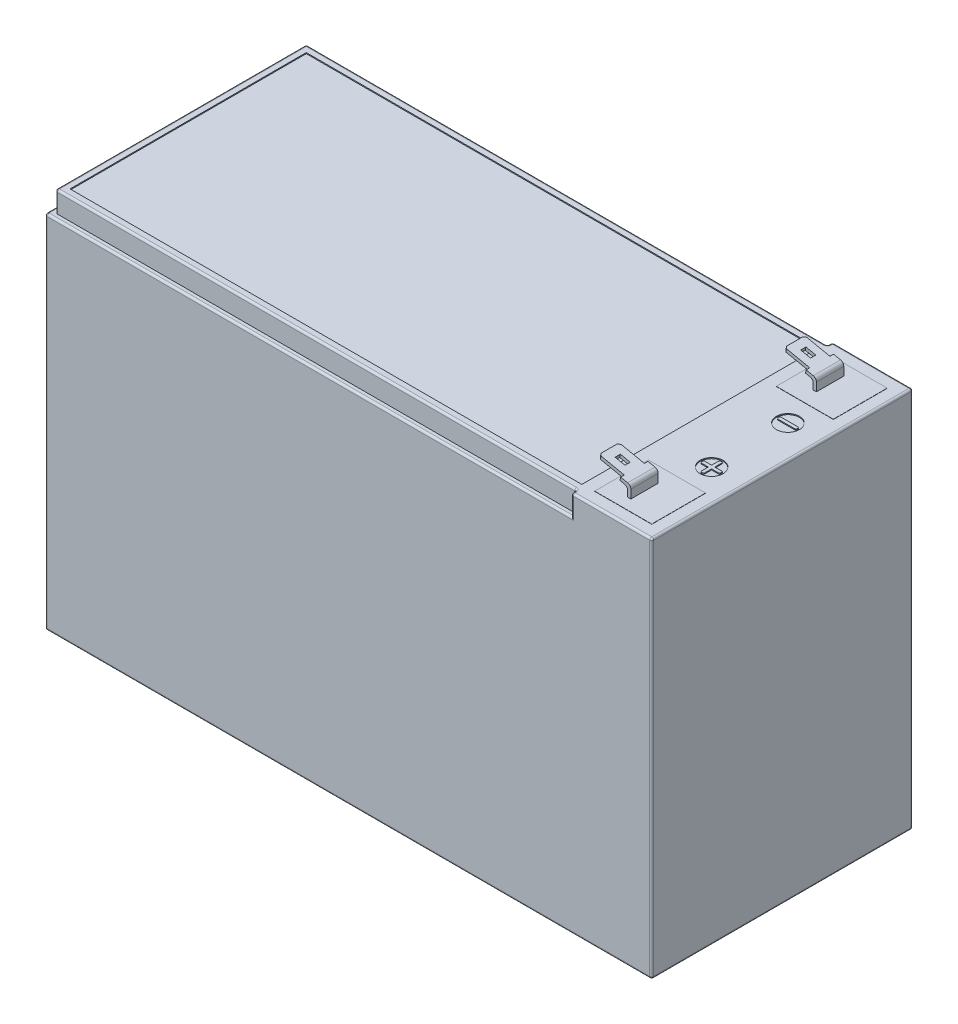
SolidWorks part; units mm, degrees
ref_plane "Front Plane" through (0, 0, 0) normal (0, 0, 1) x (1, 0, 0)
ref_plane "Top Plane" through (0, 0, 0) normal (0, 1, 0) x (1, 0, 0)
ref_plane "Right Plane" through (0, 0, 0) normal (1, 0, 0) x (0, 0, -1)
sketch "Sketch1" plane through (0, 0, 0) normal (0, 1, 0) x (1, 0, 0)
  line L1 (-75.0564, 43.5611) -> (75.9436, 43.5611)
  line L2 (-75.0564, 43.5611) -> (-75.0564, -21.4389)
  line L3 (-75.0564, -21.4389) -> (75.9436, -21.4389)
  line L4 (75.9436, 43.5611) -> (75.9436, -21.4389)
  dimension "D1" = 151
  dimension "D2" = 65
extrude "Boss-Extrude1" add sketch "Sketch1" along normal blind 95
ref_plane "Plane1" through (0, 0, 15.4389) normal (0, 0, 1) x (1, 0, 0)
sketch "Sketch2" plane through (0, 0, 15.4389) normal (0, 0, 1) x (1, 0, 0)
  line L0 (63.9436, 95) -> (63.9436, 97.3257)
  line L1 (-75.0564, 95) -> (75.9436, 95) construction
  line L2 (63.9436, 97.3257) -> (55.7698, 99.03)
  line L3 (55.7698, 99.03) -> (55.9331, 99.8131)
  line L4 (55.9331, 99.8131) -> (64.7436, 97.9761)
  line L5 (64.7436, 97.9761) -> (64.7436, 95)
  line L6 (64.7436, 95) -> (63.9436, 95)
  line L7 (75.9436, 95) -> (75.9436, 0) construction
  dimension "D1" = 12
  dimension "D2" = 9
  dimension "D3" = 0.8
  dimension "D4" = 0.8
extrude "Boss-Extrude2" add sketch "Sketch2" against normal blind 6.8
ref_plane "Plane2" through (0, 0, -11.0611) normal (0, 0, 1) x (1, 0, 0)
sketch "Sketch4" plane through (22.274, 106.8309, 0) normal (0.2041, 0.9789, 0) x (0.9789, -0.2041, 0)
  line L0 (40.7829, -8.6389) -> (40.7829, -9.5389)
  line L1 (43.3829, -8.6389) -> (34.3829, -8.6389) construction
  line L2 (40.7829, -9.5389) -> (34.3829, -9.5389)
  line L3 (34.3829, -8.6389) -> (34.3829, -15.4389) construction
  line L4 (34.3829, -9.5389) -> (34.3829, -8.6389)
  line L5 (34.3829, -8.6389) -> (40.7829, -8.6389)
  line L6 (40.7829, -14.5389) -> (40.7829, -15.4389)
  line L7 (-52.25, -15.4389) -> (52.25, -15.4389) construction
  line L8 (40.7829, -14.5389) -> (34.3829, -14.5389)
  line L9 (34.3829, -14.5389) -> (34.3829, -15.4389)
  line L10 (34.3829, -15.4389) -> (40.7829, -15.4389)
  line L12 (36.5829, -11.3889) -> (39.0829, -11.3889)
  line L13 (36.5829, -11.3889) -> (36.5829, -12.6889)
  line L14 (36.5829, -12.6889) -> (39.0829, -12.6889)
  line L15 (39.0829, -11.3889) -> (39.0829, -12.6889)
  dimension "D1" = 0.9
  dimension "D2" = 0.9
  dimension "D3" = 6.4
  dimension "D4" = 2.2
  dimension "D5" = 2.5
  dimension "D6" = 1.3
  dimension "D7" = 1.85
  dimension "D8" = 1.85
extrude "Cut-Extrude1" cut sketch "Sketch4" against normal up to next
chamfer "Chamfer1" distance 0.5 angle 45 2 edges at (55.8514, 99.4215, 9.5389) (55.8514, 99.4215, 14.5389)
fillet "Fillet1" radius 1 2 edges at (63.9436, 97.3257, 12.0389) (64.7436, 97.9761, 12.0389)
mirror "Mirror1" about plane through (0, 0, -11.0611) normal (0, 0, 1) of "Fillet1", "Chamfer1", "Cut-Extrude1", "Boss-Extrude2"
sketch "Sketch5" plane through (0, 95, 0) normal (0, 1, 0) x (1, 0, 0)
  line L0 (55.9436, -21.4389) -> (55.9436, -20.1389)
  line L1 (-75.0564, -21.4389) -> (75.9436, -21.4389) construction
  line L2 (55.9436, -20.1389) -> (-73.7564, -20.1389)
  line L3 (-73.7564, -20.1389) -> (-73.7564, 42.2611)
  line L4 (-73.7564, 42.2611) -> (55.9436, 42.2611)
  line L5 (55.9436, 42.2611) -> (55.9436, 43.5611)
  line L6 (75.9436, 43.5611) -> (-75.0564, 43.5611) construction
  line L7 (55.9436, 43.5611) -> (-75.0564, 43.5611)
  line L8 (-75.0564, 43.5611) -> (-75.0564, -21.4389)
  line L9 (-75.0564, -21.4389) -> (55.9436, -21.4389)
  line L10 (75.9436, -21.4389) -> (75.9436, 43.5611) construction
  dimension "D1" = 1.3
  dimension "D2" = 1.3
  dimension "D3" = 1.3
  dimension "D4" = 20
  dimension "D5" = 20
extrude "Cut-Extrude2" cut sketch "Sketch5" against normal blind 5.2
fillet "Fillet2" radius 0.5 25 edges at (0.4436, 0, -43.5611) (-75.0564, 44.9, -43.5611) (-75.0564, 0, -11.0611) (-75.0564, 44.9, 21.4389) (75.9436, 0, -11.0611) (0.4436, 0, 21.4389) (75.9436, 47.5, -43.5611) (65.9436, 95, -43.5611) (55.9436, 92.4, -43.5611) (55.9436, 92.4, -42.2611) (55.9436, 95, -42.9111) (-9.5564, 89.8, -43.5611) (-8.9064, 95, -42.2611) (-73.7564, 92.4, -42.2611) (-73.7564, 92.4, 20.1389) (-75.0564, 89.8, -11.0611) (55.9436, 92.4, 20.1389) (-9.5564, 89.8, 21.4389) (55.9436, 92.4, 21.4389) (75.9436, 47.5, 21.4389) (75.9436, 95, -11.0611) (65.9436, 95, 21.4389) (55.9436, 95, 20.7889) (-8.9064, 95, 20.1389) (-73.7564, 95, -11.0611)
sketch "Sketch6" plane through (0, 95, 0) normal (0, 1, 0) x (1, 0, 0)
  line L0 (-73.7564, -19.6389) -> (-73.7564, 41.7611) construction
  line L1 (-71.9564, 40.4611) -> (55.4436, 40.4611)
  line L2 (-71.9564, 40.4611) -> (-71.9564, -18.3389)
  line L3 (-71.9564, -18.3389) -> (55.4436, -18.3389)
  line L4 (55.4436, 40.4611) -> (55.4436, -18.3389)
  line L5 (-73.2564, 42.2611) -> (55.4436, 42.2611) construction
  line L6 (55.4436, -20.1389) -> (-73.2564, -20.1389) construction
  line L7 (75.9436, 43.0611) -> (75.9436, -20.9389) construction
  line L8 (56.4436, 43.5611) -> (75.4436, 43.5611) construction
  line L9 (75.4436, -21.4389) -> (56.4436, -21.4389) construction
  line L10 (67.4436, 3.7111) -> (67.4436, 1.9611)
  line L11 (65.6936, 20.9611) -> (69.9936, 20.9611)
  line L12 (65.4436, 20.7111) -> (65.4436, 20.4111)
  line L13 (65.6936, 20.1611) -> (69.9936, 20.1611)
  line L14 (70.2436, 20.7111) -> (70.2436, 20.4111)
  line L15 (67.4436, 1.9611) -> (65.6936, 1.9611)
  line L16 (65.4436, 1.7111) -> (65.4436, 1.4111)
  line L17 (65.6936, 1.1611) -> (67.4436, 1.1611)
  line L18 (67.4436, 1.1611) -> (67.4436, -0.5889)
  line L19 (67.6936, -0.8389) -> (67.9936, -0.8389)
  line L20 (68.2436, -0.5889) -> (68.2436, 1.1611)
  line L21 (68.2436, 1.1611) -> (69.9936, 1.1611)
  line L22 (70.2436, 1.4111) -> (70.2436, 1.7111)
  line L23 (69.9936, 1.9611) -> (68.2436, 1.9611)
  line L24 (68.2436, 1.9611) -> (68.2436, 3.7111)
  line L25 (67.9936, 3.9611) -> (67.6936, 3.9611)
  line L27 (72.7436, 40.3611) -> (58.5436, 40.3611)
  line L28 (72.7436, 40.3611) -> (72.7436, 26.9611)
  line L29 (72.7436, 26.9611) -> (58.5436, 26.9611)
  line L30 (58.5436, 40.3611) -> (58.5436, 26.9611)
  line L31 (72.7436, -18.2389) -> (58.5436, -18.2389)
  line L32 (72.7436, -18.2389) -> (72.7436, -4.8389)
  line L33 (72.7436, -4.8389) -> (58.5436, -4.8389)
  line L34 (58.5436, -18.2389) -> (58.5436, -4.8389)
  circle A0 centre (67.8436, 20.5611) radius 2.875
  circle A1 centre (67.8436, 1.5611) radius 2.875
  arc A2 (69.9936, 20.1611) -> (70.2436, 20.4111) centre (69.9936, 20.4111) ccw
  arc A3 (70.2436, 20.7111) -> (69.9936, 20.9611) centre (69.9936, 20.7111) ccw
  arc A4 (65.6936, 20.1611) -> (65.4436, 20.4111) centre (65.6936, 20.4111) cw
  arc A5 (65.6936, 20.9611) -> (65.4436, 20.7111) centre (65.6936, 20.7111) ccw
  arc A6 (65.6936, 1.1611) -> (65.4436, 1.4111) centre (65.6936, 1.4111) cw
  arc A7 (65.4436, 1.7111) -> (65.6936, 1.9611) centre (65.6936, 1.7111) cw
  arc A8 (67.6936, -0.8389) -> (67.4436, -0.5889) centre (67.6936, -0.5889) cw
  arc A9 (67.9936, -0.8389) -> (68.2436, -0.5889) centre (67.9936, -0.5889) ccw
  arc A10 (69.9936, 1.1611) -> (70.2436, 1.4111) centre (69.9936, 1.4111) ccw
  arc A11 (70.2436, 1.7111) -> (69.9936, 1.9611) centre (69.9936, 1.7111) ccw
  arc A12 (68.2436, 3.7111) -> (67.9936, 3.9611) centre (67.9936, 3.7111) ccw
  arc A13 (67.6936, 3.9611) -> (67.4436, 3.7111) centre (67.6936, 3.7111) ccw
  dimension "D5" = 5.75
  dimension "D8" = 5.75
  dimension "D27" = 0.25
  dimension "D1" = 1.8
  dimension "D2" = 1.8
  dimension "D3" = 1.8
  dimension "D4" = 20.5
  dimension "D6" = 8.1
  dimension "D7" = 23
  dimension "D9" = 8.1
  dimension "D10" = 23
  dimension "D11" = 0.4
  dimension "D12" = 0.4
  dimension "D13" = 2.4
  dimension "D14" = 2.4
  dimension "D15" = 0.4
  dimension "D16" = 0.4
  dimension "D17" = 0.4
  dimension "D18" = 0.4
  dimension "D19" = 0.4
  dimension "D20" = 0.4
  dimension "D21" = 0.4
  dimension "D22" = 0.4
  dimension "D23" = 2.4
  dimension "D24" = 2.4
  dimension "D25" = 2.4
  dimension "D26" = 2.4
  dimension "D28" = 3.2
  dimension "D29" = 3.2
  dimension "D30" = 14.2
  dimension "D31" = 13.4
  dimension "D32" = 3.2
  dimension "D33" = 3.2
  dimension "D34" = 14.2
  dimension "D35" = 13.4
extrude "Cut-Extrude3" cut sketch "Sketch6" against normal blind 0.25
sketch "Sketch7" plane through (0, 94.75, 0) normal (0, 1, 0) x (1, 0, 0)
  line L0 (58.5436, 26.9611) -> (72.7436, 26.9611) construction
  line L1 (72.7436, 26.9611) -> (72.7436, 40.3611) construction
  line L2 (58.5436, 40.3611) -> (58.5436, 26.9611) construction
  line L3 (72.7436, 40.3611) -> (58.5436, 40.3611) construction
  line L4 (58.5436, 26.9611) -> (72.7436, 26.9611)
  line L5 (72.7436, 26.9611) -> (72.7436, 40.3611)
  line L6 (58.5436, 40.3611) -> (58.5436, 26.9611)
  line L7 (72.7436, 40.3611) -> (58.5436, 40.3611)
extrude "Boss-Extrude3" add sketch "Sketch7" along normal blind 0.3
sketch "Sketch8" plane through (0, 94.75, 0) normal (0, 1, 0) x (1, 0, 0)
  line L0 (58.5436, -18.2389) -> (72.7436, -18.2389) construction
  line L1 (72.7436, -18.2389) -> (72.7436, -4.8389) construction
  line L2 (58.5436, -4.8389) -> (58.5436, -18.2389) construction
  line L3 (72.7436, -4.8389) -> (58.5436, -4.8389) construction
  line L4 (58.5436, -18.2389) -> (72.7436, -18.2389)
  line L5 (72.7436, -18.2389) -> (72.7436, -4.8389)
  line L6 (58.5436, -4.8389) -> (58.5436, -18.2389)
  line L7 (72.7436, -4.8389) -> (58.5436, -4.8389)
extrude "Boss-Extrude4" add sketch "Sketch8" along normal blind 0.3
ref_plane "Plane3" through (0.4436, 0, 0) normal (-1, 0, 0) x (0, 0, 1)
sketch "Sketch9" plane through (0, 0, 0) normal (0, -1, 0) x (1, 0, 0)
  line L0 (-70.0564, 8.7389) -> (-70.0564, 15.9389)
  line L1 (-69.5564, 16.4389) -> (-62.3564, 16.4389)
  line L2 (-61.8564, 15.9389) -> (-61.8564, 14.9389)
  line L3 (-62.3564, 14.4389) -> (-68.0564, 14.4389)
  line L4 (-68.0564, 14.4389) -> (-68.0564, 8.7389)
  line L5 (-68.5564, 8.2389) -> (-69.5564, 8.2389)
  line L6 (-74.5564, 21.4389) -> (75.4436, 21.4389) construction
  line L7 (-75.0564, -43.0611) -> (-75.0564, 20.9389) construction
  arc A0 (-68.5564, 8.2389) -> (-68.0564, 8.7389) centre (-68.5564, 8.7389) ccw
  arc A1 (-69.5564, 8.2389) -> (-70.0564, 8.7389) centre (-69.5564, 8.7389) cw
  arc A2 (-62.3564, 14.4389) -> (-61.8564, 14.9389) centre (-62.3564, 14.9389) ccw
  arc A3 (-61.8564, 15.9389) -> (-62.3564, 16.4389) centre (-62.3564, 15.9389) ccw
  arc A4 (-69.5564, 16.4389) -> (-70.0564, 15.9389) centre (-69.5564, 15.9389) ccw
  dimension "D7" = 0.5
  dimension "D1" = 8.2
  dimension "D2" = 8.2
  dimension "D3" = 2
  dimension "D4" = 2
  dimension "D5" = 5
  dimension "D6" = 5
extrude "Boss-Extrude5" add sketch "Sketch9" along normal blind 0.5
mirror "Mirror2" about plane through (0.4436, 0, 0) normal (-1, 0, 0) of "Boss-Extrude5"
mirror "Mirror3" about plane through (0, 0, -11.0611) normal (0, 0, 1) of "Mirror2", "Boss-Extrude5"
